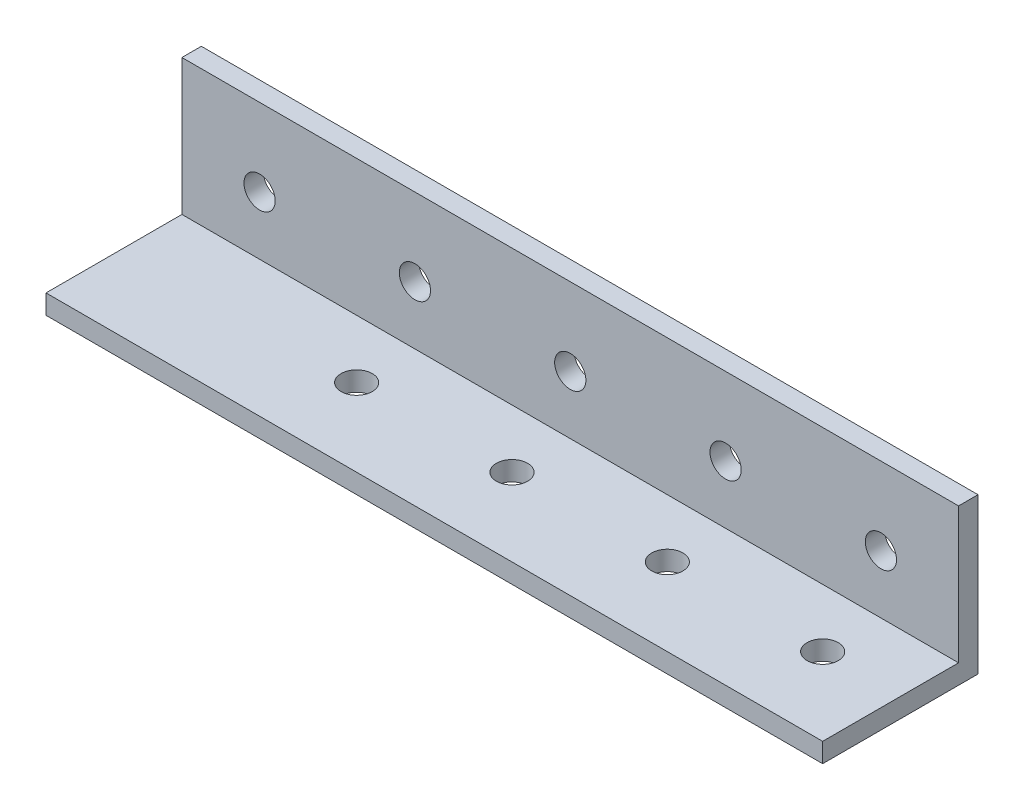
SolidWorks part; units mm, degrees
ref_plane "Front Plane" through (0, 0, 0) normal (0, 0, 1) x (1, 0, 0)
ref_plane "Top Plane" through (0, 0, 0) normal (0, 1, 0) x (1, 0, 0)
ref_plane "Right Plane" through (0, 0, 0) normal (1, 0, 0) x (0, 0, -1)
ref_plane "Plane1" through (0, 25.4, 0) normal (0, 1, 0) x (1, 0, 0)
sketch "Sketch1" plane through (0, 25.4, 0) normal (0, 1, 0) x (1, 0, 0)
  line L0 (0, 0) -> (0, -25.4)
  line L1 (0, -25.4) -> (127, -25.4)
  line L2 (127, -25.4) -> (127, 0)
  line L3 (127, 0) -> (0, 0)
extrude "Boss-Extrude1" add sketch "Sketch1" against normal blind 25.4
sketch "Sketch2" plane through (127, 0, 0) normal (1, 0, 0) x (0, 0, -1)
  line L0 (-3.175, 3.175) -> (-3.175, 25.4)
  line L1 (-3.175, 25.4) -> (-25.4, 25.4)
  line L2 (-25.4, 25.4) -> (-25.4, 3.175)
  line L3 (-25.4, 3.175) -> (-3.175, 3.175)
extrude "Cut-Extrude1" cut sketch "Sketch2" against normal through all
hole_wizard "#7 (0.201) Diameter Hole1" positions "Sketch4" profile "Sketch3" hole size "#7" standard "ANSI Inch"
sketch "Sketch4" plane through (0, 0, 0) normal (0, -1, 0) x (1, 0, 0)
  point P0 (-12.7, -12.7)
  point P1 (38.1, 12.7)
  point P2 (63.5, 12.7)
  point P3 (88.9, 12.7)
  point P4 (114.3, 12.7)
sketch "Sketch3" plane through (-12.7, 0, -12.7) normal (1, 0, 0) x (0, 0, -1)
  line L0 (0, 0) -> (0, 25.4)
  line L1 (0, 25.4) -> (2.5527, 25.4)
  line L2 (2.5527, 25.4) -> (2.5527, 0)
  line L5 (2.5527, 0) -> (0, 0)
  line L11 (0, -6.35) -> (0, 107.95) construction
  dimension "Thru Hole Dia." = 5.1054
  dimension "Thru Hole Depth" = 25.4
hole_wizard "#7 (0.201) Diameter Hole2" positions "Sketch6" profile "Sketch5" hole size "#7" standard "ANSI Inch"
sketch "Sketch6" plane through (0, 0, 3.175) normal (0, 0, 1) x (1, 0, 0)
  point P0 (12.7, 12.7)
  point P1 (38.1, 12.7)
  point P2 (63.5, 12.7)
  point P3 (88.9, 12.7)
  point P4 (114.3, 12.7)
sketch "Sketch5" plane through (12.7, 12.7, 3.175) normal (1, 0, 0) x (0, -1, 0)
  line L0 (0, 0) -> (0, 3.175)
  line L1 (0, 3.175) -> (2.5527, 3.175)
  line L2 (2.5527, 3.175) -> (2.5527, 0)
  line L5 (2.5527, 0) -> (0, 0)
  line L11 (0, -6.35) -> (0, 107.95) construction
  dimension "Thru Hole Dia." = 5.1054
  dimension "Thru Hole Depth" = 3.175
